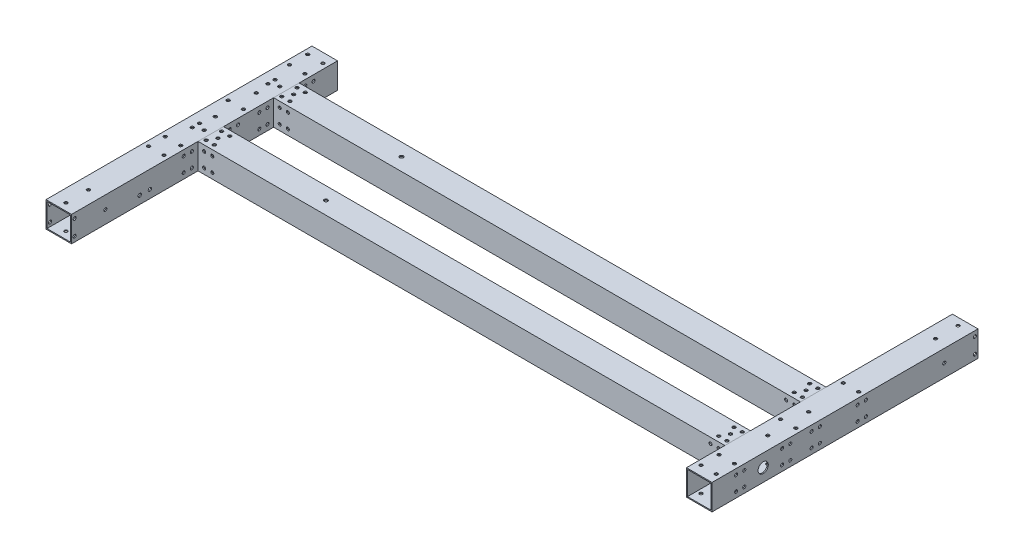
SolidWorks part; units mm, degrees
material "6061 合金"
ref_plane "前视基准面" through (0, 0, 0) normal (0, 0, 1) x (1, 0, 0)
ref_plane "上视基准面" through (0, 0, 0) normal (0, 1, 0) x (1, 0, 0)
ref_plane "右视基准面" through (0, 0, 0) normal (1, 0, 0) x (0, 0, -1)
sketch3d "3D草图1"
  line L0 (0, 0, 136.1) -> (0, 0, -123.9)
  line L1 (0, 0, 0) -> (540, 0, 0)
  line L2 (0, 0, -73.9) -> (540, 0, -73.9)
  line L3 (540, 0, -210) -> (540, 0, 50)
  dimension "D1" = 540
  dimension "D2" = 73.9
  dimension "D4" = 50
  dimension "D3" = 210
  dimension "D5" = 50
other "方形管 20X20X1(1)"
ref_plane "基准面1" through (0, 0, 0) normal (1, 0, 0) x (0, 0, -1)
sketch "草图1" plane through (0, 0, 0) normal (1, 0, 0) x (0, 0, -1)
  line L0 (-11.5, 11.5) -> (11.5, 11.5)
  line L1 (-12.5, 12.5) -> (12.5, 12.5)
  line L2 (-12.5, 12.5) -> (-12.5, -12.5)
  line L3 (-12.5, -12.5) -> (12.5, -12.5)
  line L4 (12.5, 12.5) -> (12.5, -12.5)
  line L5 (-12.5, 12.5) -> (12.5, -12.5) construction
  line L6 (-12.5, -12.5) -> (12.5, 12.5) construction
  line L7 (11.5, 11.5) -> (11.5, -11.5)
  line L8 (-11.5, -11.5) -> (11.5, -11.5)
  line L9 (-11.5, 11.5) -> (-11.5, -11.5)
  point P0 (0, 0)
  point P10 (0, 0)
  dimension "D1" = 25
  dimension "D2" = 1
sketch "草图2" plane through (552.5, 0, 0) normal (1, 0, 0) x (0, 0, -1)
  line L0 (86.4, 12.5) -> (61.4, 12.5) construction
  line L1 (86.4, 12.5) -> (61.4, 12.5) construction
  line L3 (12.5, 12.5) -> (-12.5, 12.5) construction
  line L4 (12.5, 12.5) -> (-12.5, 12.5) construction
  circle A0 centre (0, 0) radius 5
  dimension "D1" = 10
extrude "切除-拉伸1" cut sketch "草图2" against normal through all
sketch "草图3" plane through (0, 12.5, 0) normal (0, 1, 0) x (1, 0, 0)
  line L0 (0, 0) -> (125, 0) construction
  line L1 (12.5, 73.9) -> (125, 73.9) construction
  line L2 (12.5, 86.4) -> (12.5, 61.4) construction
  circle A0 centre (125, 0) radius 1.75
  circle A1 centre (125, 73.9) radius 1.75
  dimension "D1" = 3.5
  dimension "D2" = 125
extrude "切除-拉伸2" cut sketch "草图3" against normal through all
sketch "草图4" plane through (0, -12.5, 0) normal (0, -1, 0) x (1, 0, 0)
  line L0 (552.5, -210) -> (527.5, -210) construction
  line L1 (540, -210) -> (540, -181) construction
  line L2 (527.5, -210) -> (527.5, 50) construction
  circle A0 centre (532.5, -98.4) radius 1.55 construction
  circle A1 centre (520.5, -73.9) radius 1.55 construction
  circle A2 centre (516.5, -66.4) radius 1.55 construction
  circle A3 centre (524.5, -81.4) radius 1.55 construction
  circle A4 centre (516.5, -81.4) radius 1.55 construction
  circle A5 centre (532.5, -98.4) radius 1.55
  circle A6 centre (520.5, -73.9) radius 1.55
  circle A7 centre (516.5, -66.4) radius 1.55
  circle A8 centre (524.5, -81.4) radius 1.55
  circle A9 centre (516.5, -81.4) radius 1.55
  circle A10 centre (524.5, -66.4) radius 1.55 construction
  circle A11 centre (524.5, -66.4) radius 1.55
  circle A12 centre (540, -96.95) radius 1.55 construction
  circle A13 centre (547.5, -98.4) radius 1.55 construction
  circle A14 centre (540, -96.95) radius 1.55 construction
  circle A15 centre (547.5, -98.4) radius 1.55
  circle A16 centre (542, -77.4) radius 1.55 construction
  circle A17 centre (542, -70.4) radius 1.55 construction
  circle A18 centre (534, -73.9) radius 1.55 construction
  circle A19 centre (542, -77.4) radius 1.55 construction
  circle A20 centre (542, -70.4) radius 1.55 construction
  circle A21 centre (534, -73.9) radius 1.55 construction
  circle A22 centre (540, -16.95) radius 1.55 construction
  circle A23 centre (547.5, -36.95) radius 1.55 construction
  circle A24 centre (532.5, -36.95) radius 1.55 construction
  circle A25 centre (540, -56.95) radius 1.55 construction
  circle A26 centre (540, -16.95) radius 1.55
  circle A27 centre (547.5, -36.95) radius 1.55
  circle A28 centre (532.5, -36.95) radius 1.55
  circle A29 centre (540, -56.95) radius 1.55
  circle A30 centre (516.5, 7.5) radius 1.55 construction
  circle A31 centre (524.5, 7.5) radius 1.55 construction
  circle A32 centre (547.5, 23.05) radius 1.55 construction
  circle A33 centre (532.5, 23.05) radius 1.55 construction
  circle A34 centre (516.5, 7.5) radius 1.55
  circle A35 centre (524.5, 7.5) radius 1.55
  circle A36 centre (547.5, 23.05) radius 1.55
  circle A37 centre (532.5, 23.05) radius 1.55
  circle A38 centre (520.5, 0) radius 1.55 construction
  circle A39 centre (520.5, 0) radius 1.55
  circle A40 centre (524.5, -7.5) radius 1.55 construction
  circle A41 centre (516.5, -7.5) radius 1.55 construction
  circle A42 centre (524.5, -7.5) radius 1.55
  circle A43 centre (516.5, -7.5) radius 1.55
  circle A44 centre (542, 3.5) radius 1.55 construction
  circle A45 centre (542, -3.5) radius 1.55 construction
  circle A46 centre (534, 0) radius 1.55 construction
  circle A47 centre (542, 3.5) radius 1.55 construction
  circle A48 centre (542, -3.5) radius 1.55 construction
  circle A49 centre (534, 0) radius 1.55 construction
  circle A52 centre (540, -203) radius 1.55
  circle A53 centre (540, -181) radius 1.55
  circle A54 centre (-7.5, 24.5) radius 1.55 construction
  circle A55 centre (0, 23.05) radius 1.55 construction
  circle A56 centre (-7.5, 24.5) radius 1.55
  circle A57 centre (0, 23.05) radius 1.55
  circle A58 centre (7.5, 24.5) radius 1.55 construction
  circle A59 centre (7.5, 24.5) radius 1.55
  circle A60 centre (6, 0) radius 1.55 construction
  circle A61 centre (-2, -3.5) radius 1.55 construction
  circle A62 centre (-2, 3.5) radius 1.55 construction
  circle A63 centre (6, 0) radius 1.55
  circle A64 centre (-2, -3.5) radius 1.55
  circle A65 centre (-2, 3.5) radius 1.55
  circle A66 centre (7.5, -36.95) radius 1.55 construction
  circle A67 centre (-7.5, -36.95) radius 1.55 construction
  circle A68 centre (0, -16.95) radius 1.55 construction
  circle A69 centre (7.5, -36.95) radius 1.55
  circle A70 centre (-7.5, -36.95) radius 1.55
  circle A71 centre (0, -16.95) radius 1.55
  circle A72 centre (0, -56.95) radius 1.55 construction
  circle A73 centre (0, -56.95) radius 1.55
  dimension "D3" = 3.1
  dimension "D1" = 22
  dimension "D2" = 7
extrude "切除-拉伸3" cut sketch "草图4" against normal through all
sketch "草图5" plane through (0, -12.5, 0) normal (0, -1, 0) x (1, 0, 0)
  line L0 (0, 136.1) -> (0, 129.1) construction
  line L1 (12.5, 136.1) -> (-12.5, 136.1) construction
  circle A0 centre (15.5, 7.5) radius 1.55 construction
  circle A1 centre (23.5, 7.5) radius 1.55 construction
  circle A2 centre (15.5, 7.5) radius 1.55
  circle A3 centre (23.5, 7.5) radius 1.55
  circle A4 centre (15.5, -7.5) radius 1.55 construction
  circle A5 centre (23.5, -7.5) radius 1.55 construction
  circle A6 centre (19.5, 0) radius 1.55 construction
  circle A7 centre (15.5, -7.5) radius 1.55
  circle A8 centre (23.5, -7.5) radius 1.55
  circle A9 centre (19.5, 0) radius 1.55
  circle A10 centre (-7.5, 24.5) radius 1.55 construction
  circle A11 centre (7.5, 24.5) radius 1.55 construction
  circle A12 centre (-7.5, 24.5) radius 1.55
  circle A13 centre (7.5, 24.5) radius 1.55
  circle A14 centre (-2, 3.5) radius 1.55 construction
  circle A15 centre (6, 0) radius 1.55 construction
  circle A16 centre (-2, -3.5) radius 1.55 construction
  circle A17 centre (-2, 3.5) radius 1.55
  circle A18 centre (6, 0) radius 1.55
  circle A19 centre (-2, -3.5) radius 1.55
  circle A20 centre (7.5, -36.95) radius 1.55 construction
  circle A21 centre (-7.5, -36.95) radius 1.55 construction
  circle A22 centre (0, -16.95) radius 1.55 construction
  circle A23 centre (7.5, -36.95) radius 1.55
  circle A24 centre (-7.5, -36.95) radius 1.55
  circle A25 centre (0, -16.95) radius 1.55
  circle A26 centre (-7.5, -96.95) radius 1.55 construction
  circle A27 centre (7.5, -96.95) radius 1.55 construction
  circle A28 centre (-2, -77.4) radius 1.55 construction
  circle A29 centre (-2, -70.4) radius 1.55 construction
  circle A30 centre (0, -56.95) radius 1.55 construction
  circle A31 centre (-7.5, -96.95) radius 1.55
  circle A32 centre (7.5, -96.95) radius 1.55
  circle A33 centre (-2, -77.4) radius 1.55
  circle A34 centre (-2, -70.4) radius 1.55
  circle A35 centre (0, -56.95) radius 1.55
  circle A36 centre (6, -73.9) radius 1.55 construction
  circle A37 centre (6, -73.9) radius 1.55
  circle A38 centre (15.5, -81.4) radius 1.55 construction
  circle A39 centre (23.5, -81.4) radius 1.55 construction
  circle A40 centre (19.5, -73.9) radius 1.55 construction
  circle A41 centre (15.5, -66.4) radius 1.55 construction
  circle A42 centre (23.5, -66.4) radius 1.55 construction
  circle A43 centre (15.5, -81.4) radius 1.55
  circle A44 centre (23.5, -81.4) radius 1.55
  circle A45 centre (19.5, -73.9) radius 1.55
  circle A46 centre (15.5, -66.4) radius 1.55
  circle A47 centre (23.5, -66.4) radius 1.55
  circle A50 centre (0, 107.1) radius 1.55
  circle A51 centre (0, 129.1) radius 1.55
  dimension "D3" = 3.1
  dimension "D1" = 22
  dimension "D2" = 7
extrude "切除-拉伸4" cut sketch "草图5" against normal through all
sketch "草图6" plane through (-12.5, 0, 0) normal (-1, 0, 0) x (0, 0, 1)
  line L0 (136.1, -12.5) -> (136.1, 12.5) construction
  line L1 (136.1, 0) -> (127.4945, 0) construction
  line L2 (-210, -12.5) -> (-210, 12.5) construction
  line L3 (-210, 0) -> (-195.7593, 0) construction
  circle A2 centre (133.1, -7.5) radius 1.55
  circle A3 centre (103.1, 0) radius 1.55
  circle A6 centre (-207, -7.5) radius 1.55
  circle A7 centre (-177, 0) radius 1.55
  circle A8 centre (133.1, 7.5) radius 1.55
  circle A9 centre (-207, 7.5) radius 1.55
  dimension "D4" = 3.1
  dimension "D8" = 3.1
  dimension "D1" = 3
  dimension "D2" = 3
  dimension "D3" = 15
  dimension "D5" = 30
  dimension "D6" = 15
  dimension "D7" = 30
extrude "切除-拉伸5" cut sketch "草图6" against normal through all
sketch "草图7" plane through (0, 0, -86.4) normal (0, 0, -1) x (-1, 0, 0)
  line L0 (-270, 12.5) -> (-270, -31.5568) construction
  line L1 (-527.5, 12.5) -> (-12.5, 12.5) construction
  circle A0 centre (-513.5, 7) radius 1.5 construction
  circle A1 centre (-513.5, -7) radius 1.5 construction
  circle A2 centre (-521.5, 7) radius 1.5 construction
  circle A3 centre (-521.5, -7) radius 1.5 construction
  circle A4 centre (-513.5, 7) radius 1.5
  circle A5 centre (-513.5, -7) radius 1.5
  circle A6 centre (-521.5, 7) radius 1.5
  circle A7 centre (-521.5, -7) radius 1.5
  circle A8 centre (-18.5, -7) radius 1.5
  circle A9 centre (-18.5, 7) radius 1.5
  circle A10 centre (-26.5, -7) radius 1.5
  circle A11 centre (-26.5, 7) radius 1.5
extrude "切除-拉伸6" cut sketch "草图7" against normal through all
sketch "草图10" plane through (527.5, 0, 0) normal (-1, 0, 0) x (0, 0, 1)
  line L0 (-73.9, 12.5) -> (-73.9, -12.5) construction
  line L1 (-86.4, 12.5) -> (-61.4, 12.5) construction
  line L2 (-210, -12.5) -> (50, -12.5) construction
  line L3 (-36.95, -12.5) -> (-36.95, 23.6249) construction
  circle A0 centre (-92.4, -7) radius 1.5 construction
  circle A1 centre (-100.4, -7) radius 1.5 construction
  circle A2 centre (-100.4, 7) radius 1.5 construction
  circle A3 centre (-92.4, 7) radius 1.5 construction
  circle A4 centre (-92.4, -7) radius 1.5
  circle A5 centre (-100.4, -7) radius 1.5
  circle A6 centre (-100.4, 7) radius 1.5
  circle A7 centre (-92.4, 7) radius 1.5
  circle A8 centre (-55.4, 7) radius 1.5
  circle A9 centre (-47.4, 7) radius 1.5
  circle A10 centre (-47.4, -7) radius 1.5
  circle A11 centre (-55.4, -7) radius 1.5
  circle A12 centre (18.5, 7) radius 1.5
  circle A13 centre (26.5, 7) radius 1.5
  circle A14 centre (26.5, -7) radius 1.5
  circle A15 centre (18.5, -7) radius 1.5
  circle A16 centre (-18.5, -7) radius 1.5
  circle A17 centre (-26.5, -7) radius 1.5
  circle A18 centre (-26.5, 7) radius 1.5
  circle A19 centre (-18.5, 7) radius 1.5
sketch "草图11" plane through (12.5, 0, 0) normal (1, 0, 0) x (0, 0, -1)
  line L0 (123.9, -12.5) -> (-136.1, -12.5) construction
  circle A2 centre (-69.5, -4.7) radius 1.65
  circle A3 centre (-59.5, -4.7) radius 1.65
  dimension "D3" = 3.3
  dimension "D1" = 10
  dimension "D2" = 7.8
  dimension "D4" = 69.5
extrude "切除-拉伸11" cut sketch "草图10" against normal through all and the other way through all
extrude "切除-拉伸12" cut sketch "草图11" against normal through all
sketch "草图12" plane through (0, -12.5, 0) normal (0, -1, 0) x (1, 0, 0)
  circle A0 centre (547.5, 40.75) radius 1.55 construction
  circle A1 centre (532.5, 40.75) radius 1.55 construction
  circle A2 centre (547.5, 40.75) radius 1.55
  circle A3 centre (532.5, 40.75) radius 1.55
  circle A5 centre (-7.5, 40.75) radius 1.55 construction
  circle A7 centre (-7.5, 40.75) radius 1.55
  circle A8 centre (7.5, 40.75) radius 1.55 construction
  circle A9 centre (7.5, 40.75) radius 1.55
extrude "切除-拉伸13" cut sketch "草图12" against normal through all
sketch "草图13" plane through (0, -12.5, 0) normal (0, -1, 0) x (1, 0, 0)
  line L0 (12.5, -123.9) -> (-12.5, -123.9) construction
  line L1 (0, -123.9) -> (0, -111.8721) construction
  circle A0 centre (7.5, -114.65) radius 1.55
  circle A1 centre (-7.5, -114.65) radius 1.55
  dimension "D3" = 3.1
  dimension "D1" = 15
  dimension "D2" = 9.25
extrude "切除-拉伸14" cut sketch "草图13" against normal through all
